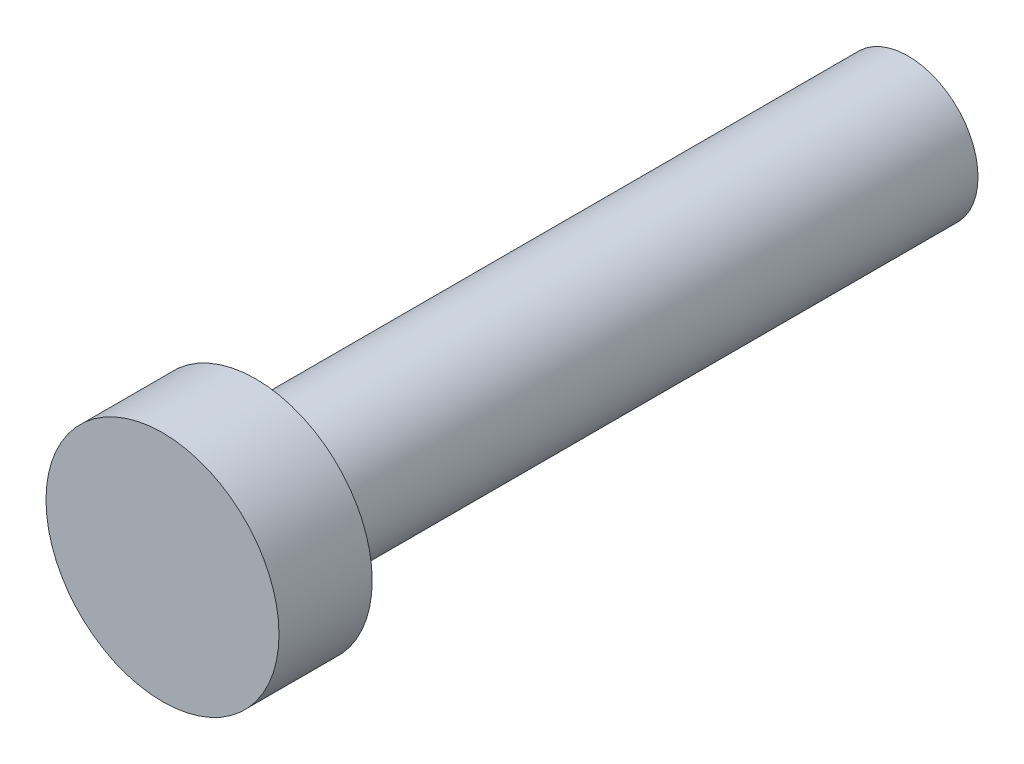
SolidWorks part; units mm, degrees
ref_plane "Plan de face" through (0, 0, 0) normal (0, 0, 1) x (1, 0, 0)
ref_plane "Plan de dessus" through (0, 0, 0) normal (0, 1, 0) x (1, 0, 0)
ref_plane "Plan de droite" through (0, 0, 0) normal (1, 0, 0) x (0, 0, -1)
sketch "Esquisse1" plane through (0, 0, 0) normal (0, 0, 1) x (1, 0, 0)
  circle A0 centre (0, 0) radius 1.5
  dimension "D1" = 3
extrude "Boss.-Extru.1" add sketch "Esquisse1" against normal blind 14
sketch "Esquisse2" plane through (0, 0, 0) normal (0, 0, 1) x (1, 0, 0)
  circle A0 centre (0, 0) radius 2.5
  dimension "D1" = 5
extrude "Boss.-Extru.2" add sketch "Esquisse2" along normal blind 2
